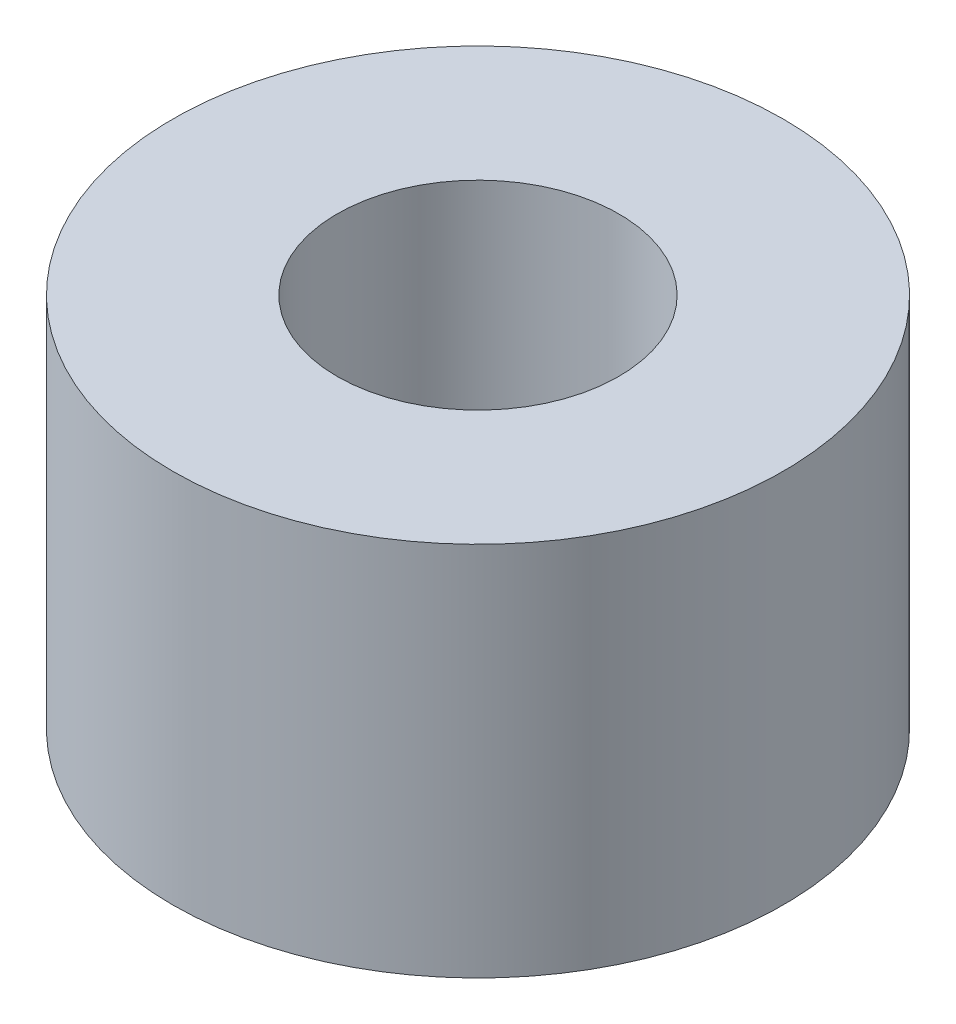
SolidWorks part; units mm, degrees
ref_plane "Plan de face" through (0, 0, 0) normal (0, 0, 1) x (1, 0, 0)
ref_plane "Plan de dessus" through (0, 0, 0) normal (0, 1, 0) x (1, 0, 0)
ref_plane "Plan de droite" through (0, 0, 0) normal (1, 0, 0) x (0, 0, -1)
sketch "Esquisse1" plane through (0, 0, 0) normal (0, 1, 0) x (1, 0, 0)
  circle A0 centre (0, 0) radius 1.5
  dimension "D1" = 3
sketch "Esquisse2" plane through (0, 0, 0) normal (0, 1, 0) x (1, 0, 0)
  circle A0 centre (0, 0) radius 3.25
  dimension "D1" = 6.5
extrude "Boss.-Extru.1" add sketch "Esquisse2" along normal blind 4
extrude "Enlèv. mat.-Extru.1" cut sketch "Esquisse1" along normal blind 28
